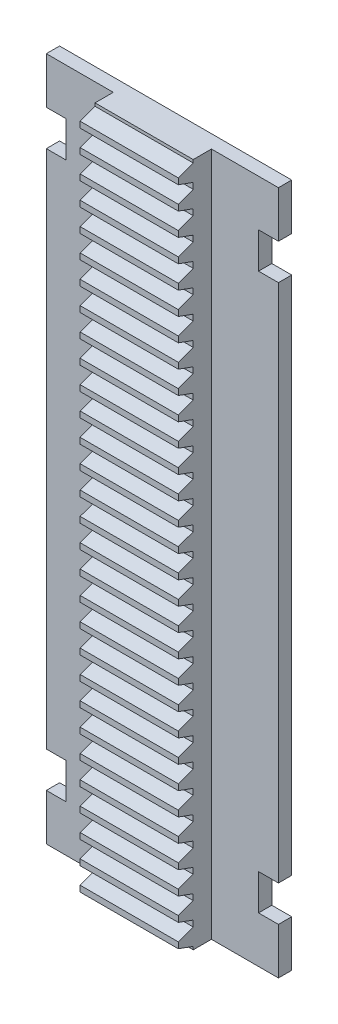
SolidWorks part; units mm, degrees
ref_plane "Front Plane" through (0, 0, 0) normal (1, 0, 0) x (0, 1, 0)
ref_plane "Top Plane" through (0, 0, 0) normal (0, 0, 1) x (0, 1, 0)
ref_plane "Right Plane" through (0, 0, 0) normal (0, 1, 0) x (-1, 0, 0)
sketch "Sketch7" plane through (0, 0, 0) normal (0, 0, 1) x (1, 0, 0)
  line L1 (-7.4, -51.6) -> (7.4, -51.6)
  line L2 (-7.4, -51.6) -> (-7.4, 51.6)
  line L3 (-7.4, 51.6) -> (7.4, 51.6)
  line L4 (7.4, -51.6) -> (7.4, 51.6)
  line L5 (-7.4, -51.6) -> (7.4, 51.6) construction
  line L6 (-7.4, 51.6) -> (7.4, -51.6) construction
  point P0 (0, 0)
  dimension "D1" = 14.8
  dimension "D2" = 103.2
extrude "Boss-Extrude4" add sketch "Sketch7" along normal blind 7 contours L4 L3 L2 L1
sketch "Sketch9" plane through (7.4, 0, 0) normal (1, 0, 0) x (0, 1, 0)
  line L3 (-52.87, 7) -> (-52.0511, 4.75)
  line L5 (-52.0511, 4.75) -> (-51.1511, 4.75)
  line L6 (-51.1511, 4.75) -> (-50.3321, 7)
  line L7 (-50.3321, 7) -> (-52.87, 7)
  line L8 (-51.6011, 7) -> (-51.6011, 4.75) construction
  line L9 (-51.6, 7) -> (51.6, 7) construction
  dimension "D1" = 20
  dimension "D3" = 2.25
  dimension "D4" = 0.9
  dimension "D5" = 2.5379
extrude "Cut-Extrude2" cut sketch "Sketch9" against normal blind 15 contours L3 L5 L6 L7
pattern_linear "LPattern1" count 31 spacing 3.44 along (0, 1, 0) of "Cut-Extrude2"
sketch "Sketch10" plane through (7.4, 0, 0) normal (1, 0, 0) x (0, 1, 0)
  line L1 (-51.6, 2) -> (51.6, 2)
  line L2 (-51.6, 2) -> (-51.6, 0)
  line L3 (-51.6, 0) -> (51.6, 0)
  line L4 (51.6, 2) -> (51.6, 0)
  dimension "D1" = 2
extrude "Boss-Extrude5" add sketch "Sketch10" along normal blind 10.1
sketch "Sketch11" plane through (-7.4, 0, 0) normal (-1, 0, 0) x (0, -1, 0)
  line L0 (51.6, 4.75) -> (51.6, 0) construction
  line L1 (-51.6, 0) -> (51.6, 0)
  line L2 (-51.6, 0) -> (-51.6, 2)
  line L3 (-51.6, 2) -> (51.6, 2)
  line L4 (51.6, 0) -> (51.6, 2)
  dimension "D1" = 2
extrude "Boss-Extrude6" add sketch "Sketch11" along normal blind 10.1
sketch "Sketch12" plane through (0, 0, 2) normal (0, 0, 1) x (1, 0, 0)
  line L0 (7.4, 51.6) -> (7.4, -51.6) construction
  line L1 (14.5, -39.2) -> (19.9, -39.2)
  line L2 (14.5, -39.2) -> (14.5, -44.6)
  line L3 (14.5, -44.6) -> (19.9, -44.6)
  line L4 (19.9, -39.2) -> (19.9, -44.6)
  line L5 (17.5, -51.6) -> (7.4, -51.6) construction
  line L6 (17.5, 0) -> (-18.1579, 0) construction
  line L7 (17.5, 51.6) -> (17.5, -51.6) construction
  line L8 (19.9, 39.2) -> (19.9, 44.6)
  line L9 (14.5, 44.6) -> (19.9, 44.6)
  line L10 (14.5, 39.2) -> (14.5, 44.6)
  line L11 (14.5, 39.2) -> (19.9, 39.2)
  line L12 (0, 51.6) -> (0, -51.6) construction
  line L13 (7.4, 51.6) -> (-7.4, 51.6) construction
  line L14 (7.4, -51.6) -> (-7.4, -51.6) construction
  line L15 (-14.5, 39.2) -> (-19.9, 39.2)
  line L16 (-14.5, 39.2) -> (-14.5, 44.6)
  line L17 (-14.5, 44.6) -> (-19.9, 44.6)
  line L18 (-19.9, 39.2) -> (-19.9, 44.6)
  line L19 (-19.9, -39.2) -> (-19.9, -44.6)
  line L20 (-14.5, -44.6) -> (-19.9, -44.6)
  line L21 (-14.5, -39.2) -> (-14.5, -44.6)
  line L22 (-14.5, -39.2) -> (-19.9, -39.2)
  dimension "D1" = 5.4
  dimension "D2" = 5.4
  dimension "D3" = 7.1
  dimension "7" = 7
extrude "Cut-Extrude3" cut sketch "Sketch12" against normal through all
